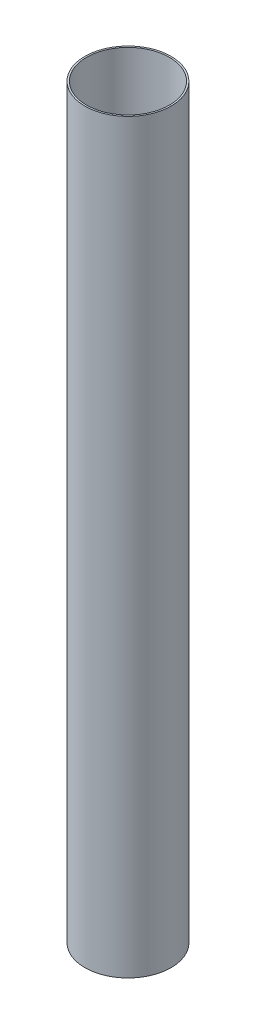
SolidWorks part; units mm, degrees
ref_plane "Front Plane" through (0, 0, 0) normal (0, 0, 1) x (1, 0, 0)
ref_plane "Top Plane" through (0, 0, 0) normal (0, 1, 0) x (1, 0, 0)
ref_plane "Right Plane" through (0, 0, 0) normal (1, 0, 0) x (0, 0, -1)
sketch "Sketch1" plane through (0, 0, 0) normal (0, 1, 0) x (1, 0, 0)
  circle A0 centre (0, 0) radius 39.624
  circle A1 centre (0, 0) radius 38.1
  dimension "D1" = 79.248
  dimension "D2" = 76.2
extrude "Boss-Extrude1" add sketch "Sketch1" along normal blind 685.8
